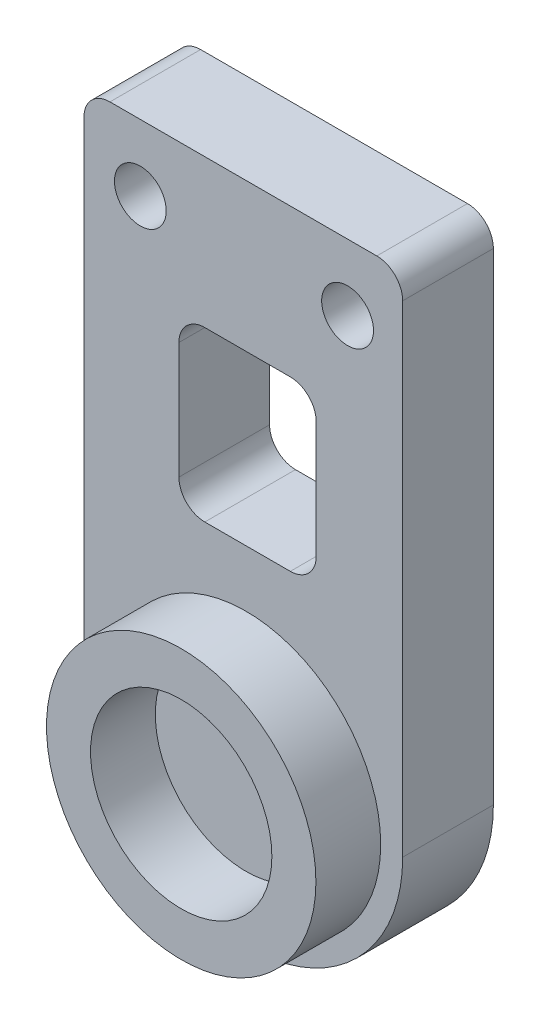
SolidWorks part; units mm, degrees
ref_plane "Front Plane" through (0, 0, 0) normal (0, 0, 1) x (1, 0, 0)
ref_plane "Top Plane" through (0, 0, 0) normal (0, 1, 0) x (1, 0, 0)
ref_plane "Right Plane" through (0, 0, 0) normal (1, 0, 0) x (0, 0, -1)
other "Graphic1"
other "object_1 (Open) -1"
ref_plane "Plane1" through (0, 0, 8) normal (0, 0, 1) x (1, 0, 0)
sketch "Sketch2" plane through (0, 0, 8) normal (0, 0, 1) x (1, 0, 0)
  line L1 (-301.2546, 240.5057) -> (-288.9546, 240.5057)
  line L2 (-301.2546, 240.5057) -> (-301.2546, 214.9057)
  line L3 (-301.2546, 214.9057) -> (-288.9546, 214.9057)
  line L4 (-288.9546, 240.5057) -> (-288.9546, 214.9057)
  dimension "D1" = 12.3
  dimension "D2" = 25.6
extrude "Boss-Extrude2" add sketch "Sketch2" along normal blind 3.5
sketch "Sketch3" plane through (0, 0, 11.5) normal (0, 0, 1) x (1, 0, 0)
  line L1 (-297.5929, 234.7929) -> (-292.2929, 234.7929)
  line L2 (-297.5929, 234.7929) -> (-297.5929, 228.2929)
  line L3 (-297.5929, 228.2929) -> (-292.2929, 228.2929)
  line L4 (-292.2929, 234.7929) -> (-292.2929, 228.2929)
  circle A0 centre (-299.082, 237.9443) radius 1
  circle A1 centre (-291.082, 237.9443) radius 1
  dimension "D1" = 8
  dimension "D3" = 6.5
  dimension "D4" = 5.3
extrude "Cut-Extrude1" cut sketch "Sketch3" against normal blind 3.5
fillet "Fillet1" radius 1 6 edges at (-292.2929, 228.2929, 9.75) (-297.5929, 228.2929, 9.75) (-297.5929, 234.7929, 9.75) (-292.2929, 234.7929, 9.75) (-301.2546, 240.5057, 9.75) (-288.9546, 240.5057, 9.75)
fillet "Fillet2" radius 6 2 edges at (-288.9546, 214.9057, 9.75) (-301.2546, 214.9057, 9.75)
sketch "Sketch4" plane through (0, 0, 11.5) normal (0, 0, 1) x (1, 0, 0)
  circle A0 centre (-295.0045, 220.9057) radius 3.5
  circle A1 centre (-295.0045, 220.9057) radius 5.2
  dimension "D1" = 7
  dimension "D3" = 10.4
  dimension "D2" = 6
extrude "Boss-Extrude3" add sketch "Sketch4" along normal blind 2.5
